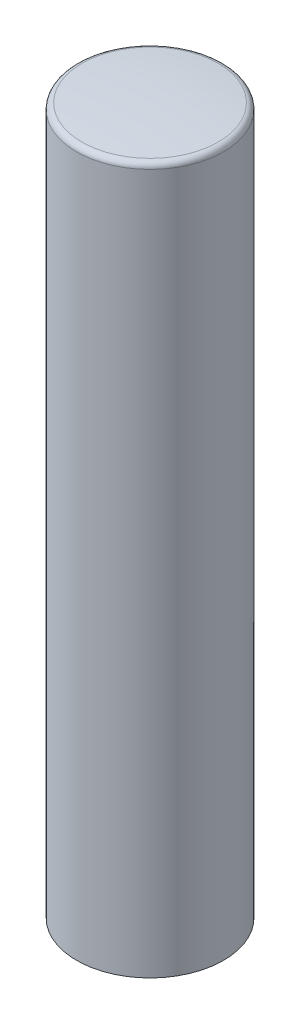
SolidWorks part; units mm, degrees
ref_plane "Front Plane" through (0, 0, 0) normal (0, 0, 1) x (1, 0, 0)
ref_plane "Top Plane" through (0, 0, 0) normal (0, 1, 0) x (1, 0, 0)
ref_plane "Right Plane" through (0, 0, 0) normal (1, 0, 0) x (0, 0, -1)
sketch "Sketch2" plane through (0, 0, 0) normal (1, 0, 0) x (0, 0, -1)
  line L0 (0, 0) -> (-2.5, 0)
  line L1 (-2.5, 0) -> (-2.5, 24)
  line L4 (0, 0) -> (0, 31.7203) construction
  line L6 (0, 0) -> (0, 24.1299)
  arc A0 (0, 24.1299) -> (-2.5, 24) centre (0, 0) ccw
  point P10 (-2.5, 24)
  dimension "D1" = 24
  dimension "D2" = 2.5
revolve "Revolve1" add sketch "Sketch2" angle 360 about L6
fillet "Fillet1" radius 0.2 1 edges at (0, 24, -2.5)
